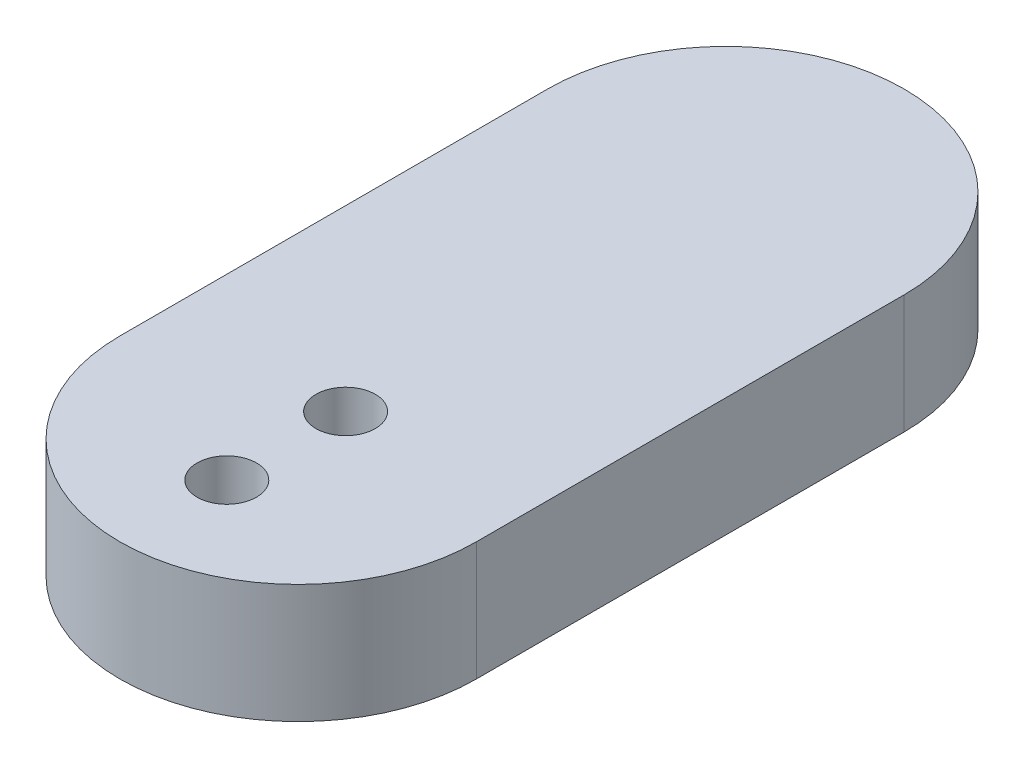
SolidWorks part; units mm, degrees
ref_plane "Front Plane" through (0, 0, 0) normal (0, 0, 1) x (1, 0, 0)
ref_plane "Top Plane" through (0, 0, 0) normal (0, 1, 0) x (1, 0, 0)
ref_plane "Right Plane" through (0, 0, 0) normal (1, 0, 0) x (0, 0, -1)
sketch "Sketch2" plane through (0, 0, 0) normal (0, 1, 0) x (1, 0, 0)
  line L0 (7.0374, 16.2319) -> (7.0374, -13.7681) construction
  line L2 (1.0374, 10.2319) -> (1.0374, -7.7681)
  line L4 (13.0374, 10.2319) -> (13.0374, -7.7681)
  line L5 (7.0374, -13.7681) -> (7.0374, -10.0181) construction
  line L6 (7.0374, -10.0181) -> (7.0374, -5.5181) construction
  arc A15 (13.0374, 10.2319) -> (1.0374, 10.2319) centre (7.0374, 10.2319) ccw
  arc A16 (1.0374, -7.7681) -> (13.0374, -7.7681) centre (7.0374, -7.7681) ccw
  dimension "D1" = 12
  dimension "D2" = 30
  dimension "D3" = 3.75
  dimension "D5" = 8.25
sketch "Sketch3" plane through (0, 0, 0) normal (0, 1, 0) x (1, 0, 0)
  line L0 (7.0374, 17.7319) -> (7.0374, -15.2681) construction
  line L1 (-0.4626, 10.2319) -> (-0.4626, -7.7681)
  line L2 (14.5374, 10.2319) -> (14.5374, -7.7681)
  line L3 (7.0374, -15.2681) -> (7.0374, -14.25) construction
  line L4 (7.0374, -14.25) -> (7.0374, -7.0181) construction
  arc A0 (14.5374, 10.2319) -> (-0.4626, 10.2319) centre (7.0374, 10.2319) ccw
  arc A1 (-0.4626, -7.7681) -> (14.5374, -7.7681) centre (7.0374, -7.7681) ccw
  dimension "D1" = 15
  dimension "D2" = 33
  dimension "D3" = 1.5
  dimension "D5" = 8.25
  dimension "D7" = 0
extrude "Boss-Extrude2" add sketch "Sketch3" along normal blind 5
extrude "Cut-Extrude2" cut sketch "Sketch2" along normal blind 3
sketch "Sketch4" plane through (0, 3, 0) normal (0, -1, 0) x (1, 0, 0)
  line L0 (1.0374, 7.7681) -> (13.0374, 7.7681) construction
  line L1 (7.0374, 13.7681) -> (7.0374, -16.2319) construction
  arc A0 (13.0374, 7.7681) -> (1.0374, 7.7681) centre (7.0374, 7.7681) ccw construction
  arc A1 (1.0374, -10.2319) -> (13.0374, -10.2319) centre (7.0374, -10.2319) ccw construction
  circle A2 centre (7.0374, 10.7681) radius 1.25
  circle A3 centre (7.0374, 5.7681) radius 1.25
  dimension "D1" = 2.5
  dimension "D3" = 5
  dimension "D2" = 3
extrude "Cut-Extrude3" cut sketch "Sketch4" against normal blind 3 and the other way through all
